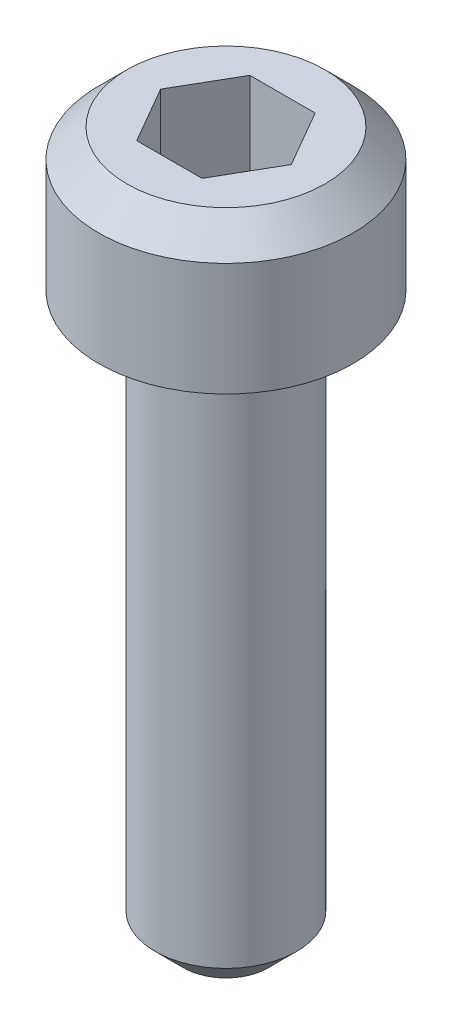
SolidWorks part; units mm, degrees
ref_plane "Front Plane" through (0, 0, 0) normal (0, 0, 1) x (1, 0, 0)
ref_plane "Top Plane" through (0, 0, 0) normal (0, 1, 0) x (1, 0, 0)
ref_plane "Right Plane" through (0, 0, 0) normal (1, 0, 0) x (0, 0, -1)
sketch "Sketch1" plane through (0, 0, 0) normal (0, 0, 1) x (1, 0, 0)
  line L0 (0, 0) -> (0, 15.7991) construction
  line L1 (0, 12.5) -> (-1.75, 12.5)
  line L2 (-2.25, 12) -> (-2.25, 10)
  line L3 (-2.25, 10) -> (-1.25, 10)
  line L4 (-1.25, 10) -> (-1.25, 0.5)
  line L5 (-0.75, 0) -> (0, 0)
  line L6 (0, 12.5) -> (0, 0)
  line L7 (-1.75, 12.5) -> (-2.25, 12)
  line L8 (-1.25, 0.5) -> (-0.75, 0)
  line L9 (0, 12.5) -> (-10, 12.5) construction
  point P4 (-2.25, 12.5)
  point P8 (-1.25, 0)
  dimension "D1" = 2.5
  dimension "D2" = 10
  dimension "D3" = 2.5
  dimension "D4" = 4.5
  dimension "D5" = 10
revolve "Revolve1" add sketch "Sketch1" angle 360 about L0
sketch "Sketch2" plane through (0, 12.5, 0) normal (0, 1, 0) x (1, 0, 0)
  line L0 (0, 0) -> (-2.9941, 0) construction
  line L1 (-1.1547, 0) -> (-0.5774, -1)
  line L2 (-0.5774, -1) -> (0.5774, -1)
  line L3 (0.5774, -1) -> (1.1547, 0)
  line L4 (1.1547, 0) -> (0.5774, 1)
  line L5 (0.5774, 1) -> (-0.5774, 1)
  line L6 (-0.5774, 1) -> (-1.1547, 0)
  line L7 (-0.5774, 1) -> (-1.5774, 0) construction
  line L8 (0, 0) -> (-10, 0) construction
  circle A0 centre (0, 0) radius 1 construction
  dimension "D1" = 2
  dimension "D2" = 45
extrude "Cut-Extrude1" cut sketch "Sketch2" against normal blind 1.5
